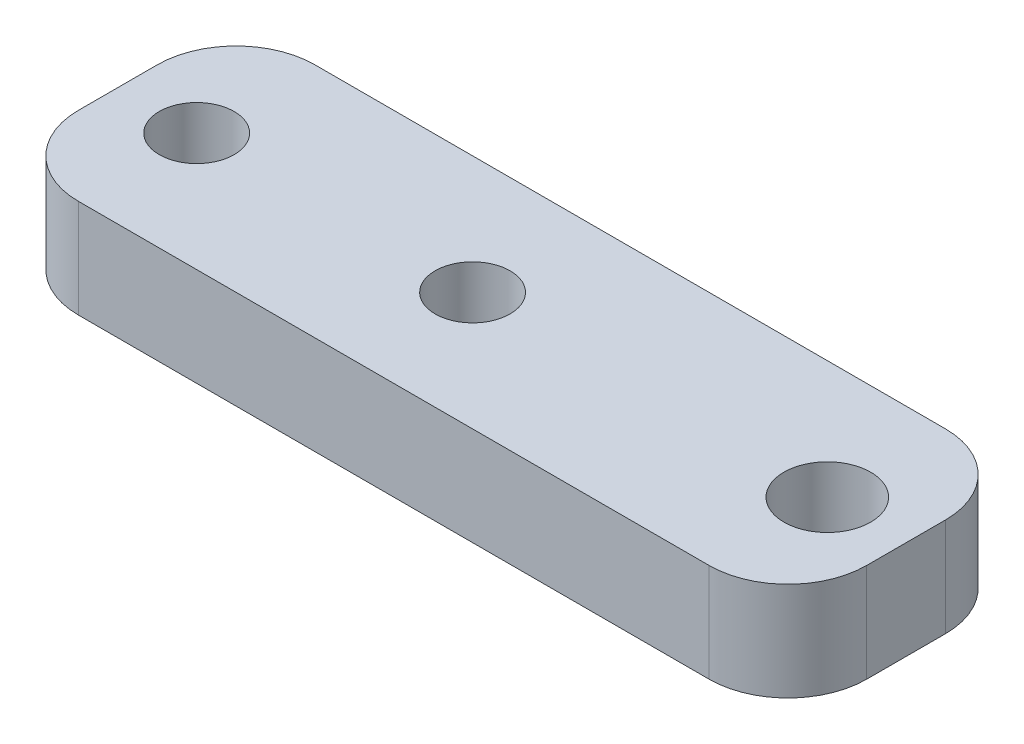
SolidWorks part; units mm, degrees
ref_plane "前视基准面" through (0, 0, 0) normal (0, 0, 1) x (1, 0, 0)
ref_plane "上视基准面" through (0, 0, 0) normal (0, 1, 0) x (1, 0, 0)
ref_plane "右视基准面" through (0, 0, 0) normal (1, 0, 0) x (0, 0, -1)
sketch "草图1" plane through (0, 0, 0) normal (0, 1, 0) x (1, 0, 0)
  line L1 (10.0306, 0) -> (30.0306, 0)
  line L2 (10.0306, 0) -> (10.0306, 6)
  line L3 (10.0306, 6) -> (30.0306, 6)
  line L4 (30.0306, 0) -> (30.0306, 6)
  dimension "D1" = 6
  dimension "D2" = 20
extrude "凸台-拉伸1" add sketch "草图1" along normal blind 2.5
sketch "草图2" plane through (0, 2.5, 0) normal (0, 1, 0) x (1, 0, 0)
  line L0 (10.0306, 6) -> (10.0306, 0) construction
  line L1 (30.0306, 0) -> (30.0306, 6) construction
  circle A0 centre (28.0306, 3) radius 1.1
  circle A1 centre (12.0306, 3) radius 0.95
  circle A2 centre (19.0306, 3) radius 0.95
  dimension "D1" = 1.9
  dimension "D2" = 1.9
  dimension "D3" = 2.2
  dimension "D4" = 2
  dimension "D5" = 2
  dimension "D6" = 9
extrude "切除-拉伸1" cut sketch "草图2" against normal through all
fillet "圆角1" radius 2 4 edges at (10.0306, 1.25, -6) (10.0306, 1.25, 0) (30.0306, 1.25, -6) (30.0306, 1.25, 0)
